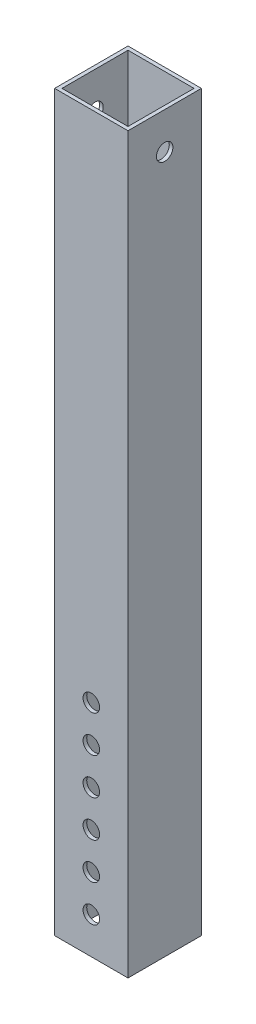
SolidWorks part; units mm, degrees
ref_plane "Front Plane" through (0, 0, 0) normal (0, 0, 1) x (1, 0, 0)
ref_plane "Top Plane" through (0, 0, 0) normal (0, 1, 0) x (1, 0, 0)
ref_plane "Right Plane" through (0, 0, 0) normal (1, 0, 0) x (0, 0, -1)
sketch "Sketch1" plane through (0, 0, 0) normal (0, 1, 0) x (1, 0, 0)
  line L0 (-9, -9) -> (-9, 9)
  line L1 (-10, -10) -> (10, -10)
  line L2 (-10, -10) -> (-10, 10)
  line L3 (-10, 10) -> (10, 10)
  line L4 (10, -10) -> (10, 10)
  line L5 (-10, -10) -> (10, 10) construction
  line L6 (-10, 10) -> (10, -10) construction
  line L7 (-9, 9) -> (9, 9)
  line L8 (9, -9) -> (9, 9)
  line L9 (-9, -9) -> (9, -9)
  point P0 (0, 0)
  dimension "D1" = 20
  dimension "D2" = 20
  dimension "D3" = 1
extrude "Boss-Extrude1" add sketch "Sketch1" along normal blind 200
sketch "Sketch2" plane through (0, 0, 10) normal (0, 0, 1) x (1, 0, 0)
  line L0 (-10, 0) -> (10, 0) construction
  circle A0 centre (0, 10) radius 2.25
  circle A3 centre (0, 20) radius 2.25
  circle A4 centre (0, 30) radius 2.25
  circle A5 centre (0, 40) radius 2.25
  circle A6 centre (0, 50) radius 2.25
  circle A7 centre (0, 60) radius 2.25
  dimension "D1" = 4.5
  dimension "D3" = 6
  dimension "D2" = 10
extrude "Cut-Extrude1" cut sketch "Sketch2" against normal through all
sketch "Sketch3" plane through (10, 0, 0) normal (1, 0, 0) x (0, 0, -1)
  line L0 (-10, 200) -> (10, 200) construction
  circle A0 centre (0, 190) radius 2.25
  dimension "D1" = 4.5
  dimension "D2" = 10
extrude "Cut-Extrude2" cut sketch "Sketch3" against normal through all
